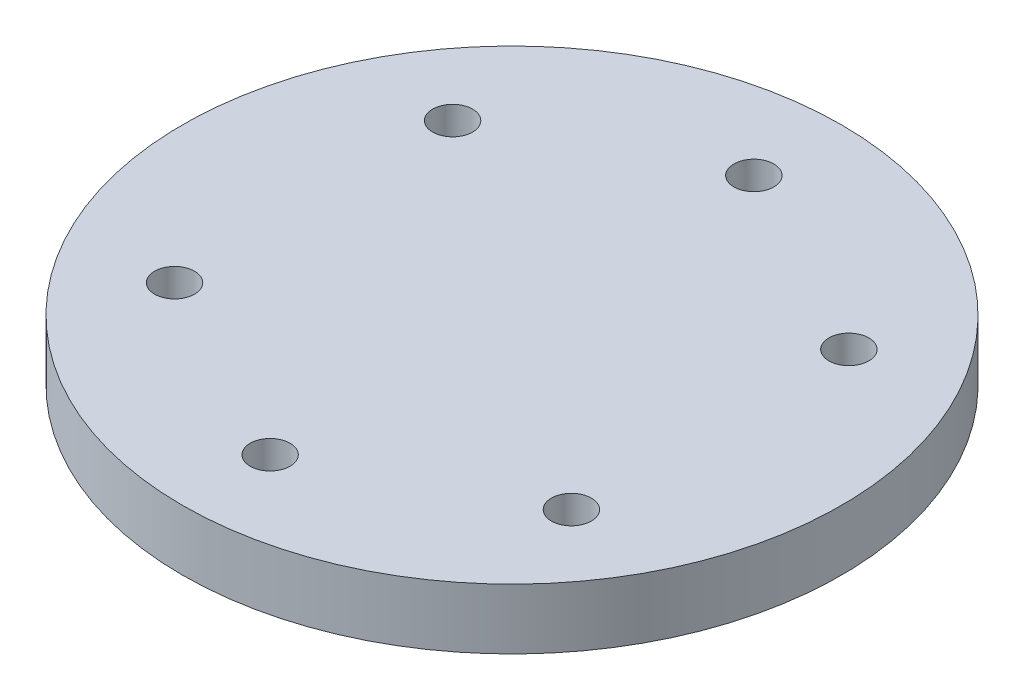
SolidWorks part; units mm, degrees
ref_plane "Front Plane" through (0, 0, 0) normal (0, 0, 1) x (1, 0, 0)
ref_plane "Top Plane" through (0, 0, 0) normal (0, 1, 0) x (1, 0, 0)
ref_plane "Right Plane" through (0, 0, 0) normal (1, 0, 0) x (0, 0, -1)
sketch "Sketch1" plane through (0, 0, 0) normal (0, 1, 0) x (1, 0, 0)
  circle A0 centre (0, 0) radius 27.25
  dimension "D1" = 54.5
extrude "Boss-Extrude1" add sketch "Sketch1" along normal blind 5
sketch "Sketch2" plane through (0, 5, 0) normal (0, 1, 0) x (1, 0, 0)
  line L0 (0, 0) -> (-27.25, 0) construction
  line L1 (0, 0) -> (-22.3219, 15.63) construction
  line L2 (0, 0) -> (22.3219, 15.63) construction
  line L3 (0, 27.25) -> (0, -27.25) construction
  line L4 (0, 0) -> (-22.3219, -15.63) construction
  line L5 (0, 0) -> (22.3219, -15.63) construction
  line L6 (0, 0) -> (27.25, 0) construction
  circle A0 centre (0, 0) radius 27.25 construction
  circle A2 centre (0, 20) radius 1.65
  circle A3 centre (-16.383, 11.4715) radius 1.65
  circle A4 centre (16.383, 11.4715) radius 1.65
  circle A5 centre (16.383, -11.4715) radius 1.65
  circle A6 centre (0, -20) radius 1.65
  circle A7 centre (-16.2709, -11.63) radius 1.65
  dimension "D2" = 20
  dimension "D3" = 3.3
  dimension "D8" = 20
  dimension "D1" = 35
  dimension "D4" = 35
  dimension "D5" = 35
  dimension "D6" = 35
  dimension "D7" = 55
  dimension "D9" = 20
  dimension "D10" = 20
  dimension "D11" = 20
  dimension "D12" = 20
extrude "Cut-Extrude1" cut sketch "Sketch2" against normal blind 10
